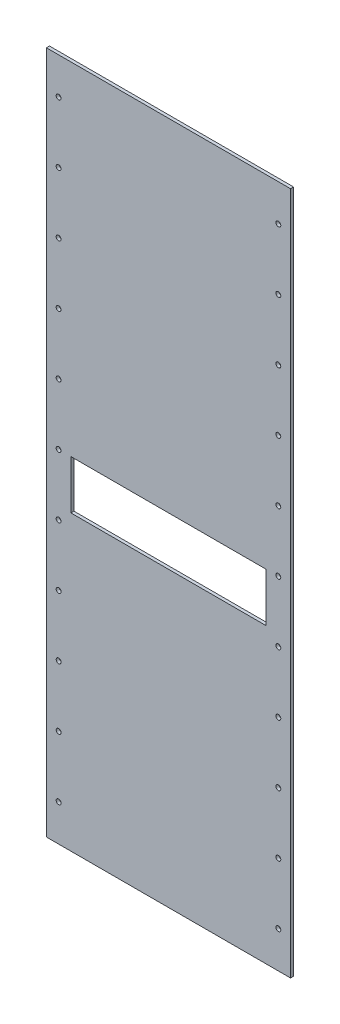
SolidWorks part; units mm, degrees
material "6061 Alloy"
ref_plane "Front" through (0, 0, 0) normal (0, 0, 1) x (1, 0, 0)
ref_plane "Top" through (0, 0, 0) normal (0, 1, 0) x (1, 0, 0)
ref_plane "Right" through (0, 0, 0) normal (1, 0, 0) x (0, 0, -1)
sketch "Sketch1" plane through (0, 0, 0) normal (0, 0, 1) x (1, 0, 0)
  line L1 (0, 0) -> (-254, 0)
  line L2 (0, 0) -> (0, 711.2)
  line L3 (0, 711.2) -> (-254, 711.2)
  line L4 (-254, 0) -> (-254, 711.2)
  dimension "D1" = 254
  dimension "D2" = 711.2
extrude "Boss-Extrude1" add sketch "Sketch1" along normal blind 3.175
hole_wizard "#10 Clearance Hole1" positions "Sketch4" profile "Sketch5" hole size "#10" standard "ANSI Inch"
sketch "Sketch4" plane through (0, 0, 3.175) normal (0, 0, 1) x (1, 0, 0)
  line L0 (0, 711.2) -> (-254, 711.2) construction
  line L2 (-254, 711.2) -> (-254, 0) construction
  line L3 (0, 0) -> (0, 711.2) construction
  point P0 (-241.3, 673.1)
  point P2 (-12.7, 673.1)
  dimension "D1" = 38.1
  dimension "D2" = 12.7
  dimension "D3" = 12.7
sketch "Sketch5" plane through (-241.3, 673.1, 3.175) normal (1, 0, 0) x (0, -1, 0)
  line L0 (0, 0) -> (0, 4.7078)
  line L1 (0, 4.7078) -> (2.5527, 3.174)
  line L2 (2.5527, 3.174) -> (2.5527, 0)
  line L5 (2.5527, 0) -> (0, 0)
  line L10 (0, 4.7078) -> (-2.5527, 3.174) construction
  line L11 (0, -6.35) -> (0, 107.95) construction
  dimension "Hole Dia." = 5.1054
  dimension "Hole Depth" = 3.174
  dimension "Drill Angle" = 118
pattern_linear "LPattern1" count 11 spacing 63.5 along (0, -1, 0) of "#10 Clearance Hole1"
sketch "Sketch7" plane through (0, 0, 0) normal (0, 0, -1) x (-1, 0, 0)
  line L0 (0, 711.2) -> (254, 711.2) construction
  line L1 (25.4, 304.8) -> (228.6, 304.8)
  line L2 (25.4, 304.8) -> (25.4, 355.6)
  line L3 (25.4, 355.6) -> (228.6, 355.6)
  line L4 (228.6, 304.8) -> (228.6, 355.6)
  line L7 (0, 0) -> (0, 711.2) construction
  point P8 (0, 355.6)
  dimension "D1" = 355.6
  dimension "D2" = 50.8
  dimension "D3" = 203.2
  dimension "D4" = 25.4
extrude "Cut-Extrude1" cut sketch "Sketch7" against normal through all
